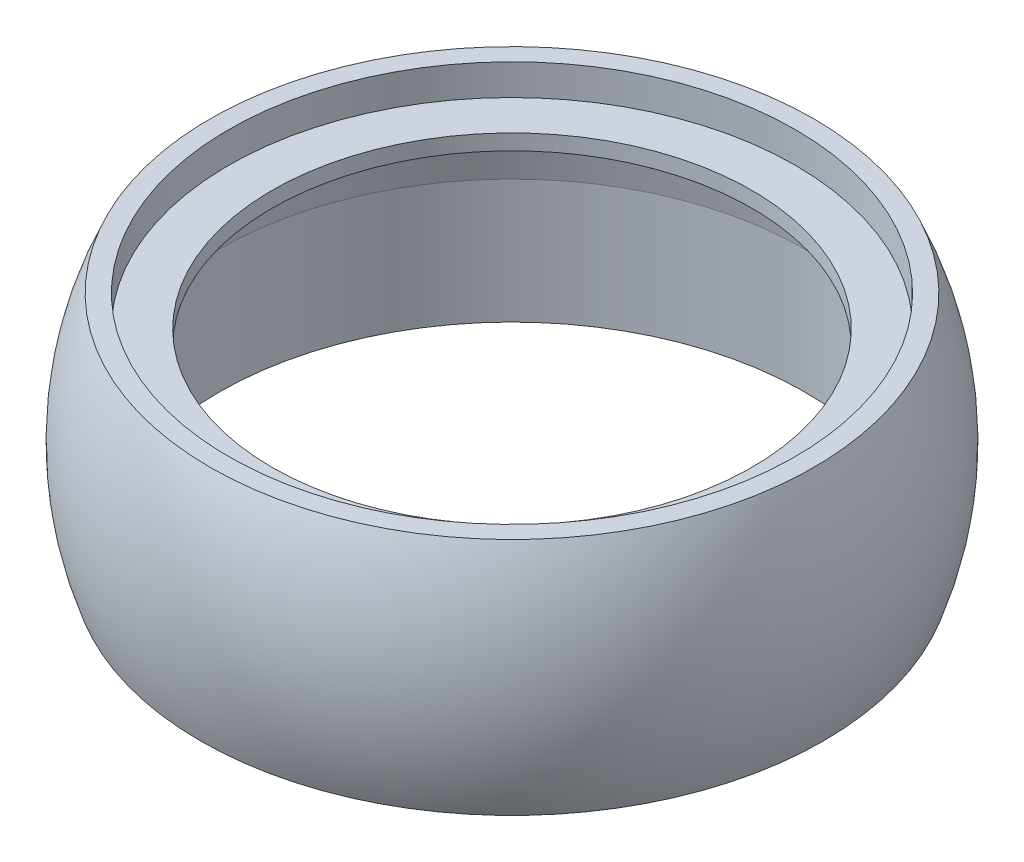
SolidWorks part; units mm, degrees
ref_plane "Front Plane" through (0, 0, 0) normal (0, 0, 1) x (1, 0, 0)
ref_plane "Top Plane" through (0, 0, 0) normal (0, 1, 0) x (1, 0, 0)
ref_plane "Right Plane" through (0, 0, 0) normal (1, 0, 0) x (0, 0, -1)
sketch "Sketch1" plane through (0, 0, 0) normal (0, 1, 0) x (1, 0, 0)
  circle A0 centre (0, 0) radius 38.75
  circle A1 centre (0, 0) radius 45.75
  dimension "D1" = 7
  dimension "D2" = 91.5
extrude "Boss-Extrude1" add sketch "Sketch1" along normal blind 2.5
sketch "Sketch3" plane through (0, 2.5, 0) normal (0, -1, 0) x (1, 0, 0)
  circle A0 centre (0, 0) radius 48.75
  circle A3 centre (0, 0) radius 45.75
  dimension "D1" = 3
  dimension "D2" = 91.5
extrude "Boss-Extrude3" add sketch "Sketch3" against normal blind 5
sketch "Sketch5" plane through (0, 0, 0) normal (0, 0, 1) x (1, 0, 0)
  line L0 (-45.8, 0) -> (-47.3, -10)
  line L1 (-45.75, 0) -> (45.75, 0) construction
  line L2 (0, 0) -> (0, -13.5689) construction
  line L3 (-47.3, -10) -> (-47.3, -30)
  line L4 (-48.7668, 0.445) -> (-50.3, -9.7763)
  line L5 (-50.3, -9.7763) -> (-50.3, -30)
  line L6 (-48.7668, 2.5) -> (-48.7668, 0.445)
  line L7 (-48.75, 2.5) -> (48.75, 2.5) construction
  line L8 (-50.3, -30) -> (-47.3, -30)
  line L9 (-48.7668, 2.5) -> (-45.8, 2.5)
  line L12 (-45.8, 2.5) -> (-45.73, 2.5)
  line L14 (-45.8, 0) -> (-45.73, 0)
  line L15 (-45.73, 2.5) -> (-45.73, 0)
  dimension "D2" = 1.5
  dimension "D1" = 10
  dimension "D3" = 94.6
  dimension "D5" = 30
  dimension "D6" = 0.07
  dimension "D4" = 3
revolve "Revolve1" add sketch "Sketch5" angle 360 about L2
sketch "Sketch8" plane through (0, 0, 0) normal (0, 0, 1) x (1, 0, 0)
  line L4 (-48.75, 7.5) -> (-48.75, 2.5)
  line L6 (-48.75, 2.5) -> (-48.7668, 2.5)
  line L7 (-48.7668, 2.5) -> (-48.7668, 0.445)
  line L8 (-48.7668, 0.445) -> (-50.3, -9.7763) construction
  line L9 (-48.7668, 2.5) -> (-48.7668, 0.445) construction
  line L10 (0, 0) -> (0, 8.386) construction
  line L11 (-48.7668, 0.445) -> (-50.3, -9.7763)
  line L12 (-50.3, -9.7763) -> (-50.3, -30)
  line L13 (-50.3, -30) -> (50.3, -30) construction
  line L14 (48.75, 7.5) -> (-48.75, 7.5) construction
  arc A0 (-48.75, 7.5) -> (-50.3, -30) centre (-3.2198, -13.1639) ccw
  dimension "D1" = 50
revolve "Revolve2" add sketch "Sketch8" angle 360 about L10
